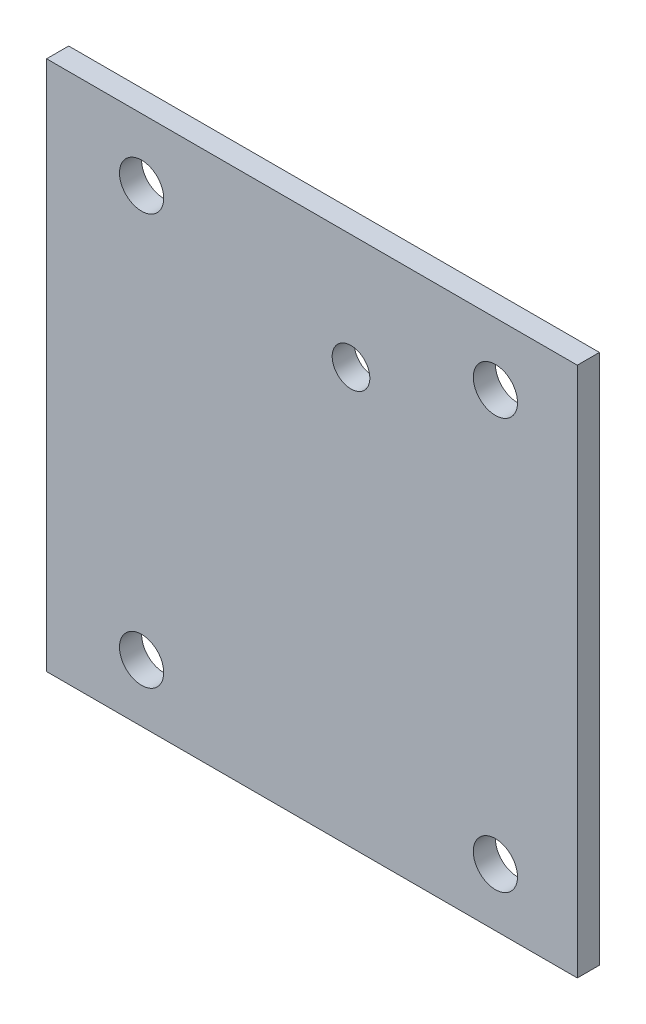
SolidWorks part; units mm, degrees
ref_plane "Front Plane" through (0, 0, 0) normal (0, 0, 1) x (1, 0, 0)
ref_plane "Top Plane" through (0, 0, 0) normal (0, 1, 0) x (1, 0, 0)
ref_plane "Right Plane" through (0, 0, 0) normal (1, 0, 0) x (0, 0, -1)
sketch "Sketch1" plane through (0, 0, 0) normal (0, 0, 1) x (1, 0, 0)
  line L1 (87.9593, 303.7762) -> (11.7593, 303.7762)
  line L2 (87.9593, 303.7762) -> (87.9593, 227.5762)
  line L3 (87.9593, 227.5762) -> (11.7593, 227.5762)
  line L4 (11.7593, 303.7762) -> (11.7593, 227.5762)
  circle A0 centre (25.4, 235.8571) radius 3.175
  circle A1 centre (25.4, 294.8214) radius 3.175
  circle A2 centre (76.2, 235.8571) radius 3.175
  circle A4 centre (76.2, 294.8214) radius 3.175
  dimension "D1" = 6.35
  dimension "D2" = 6.35
  dimension "D3" = 6.35
  dimension "D5" = 6.35
  dimension "D6" = 76.2
  dimension "D7" = 76.2
  dimension "D8" = 8.281
  dimension "D9" = 11.7593
extrude "Boss-Extrude1" add sketch "Sketch1" along normal blind 3.175
hole_wizard "1/4-28 Tapped Hole3" positions "Sketch8" profile "Sketch3" tap size "1/4-28" standard "ANSI Inch" end condition through all
sketch "Sketch8" plane through (0, 0, 3.175) normal (0, 0, 1) x (1, 0, 0)
  point P0 (55.4677, 287.2734)
sketch "Sketch3" plane through (55.4677, 287.2734, 3.175) normal (1, 0, 0) x (0, -1, 0)
  line L0 (0, 0) -> (0, 3.175)
  line L1 (0, 3.175) -> (2.7051, 3.175)
  line L2 (2.7051, 3.175) -> (2.7051, 0)
  line L5 (2.7051, 0) -> (0, 0)
  line L11 (0, -6.35) -> (0, 107.95) construction
  dimension "Thru Tap Drill Dia." = 5.4102
  dimension "Thru Tap Drill Depth" = 3.175
